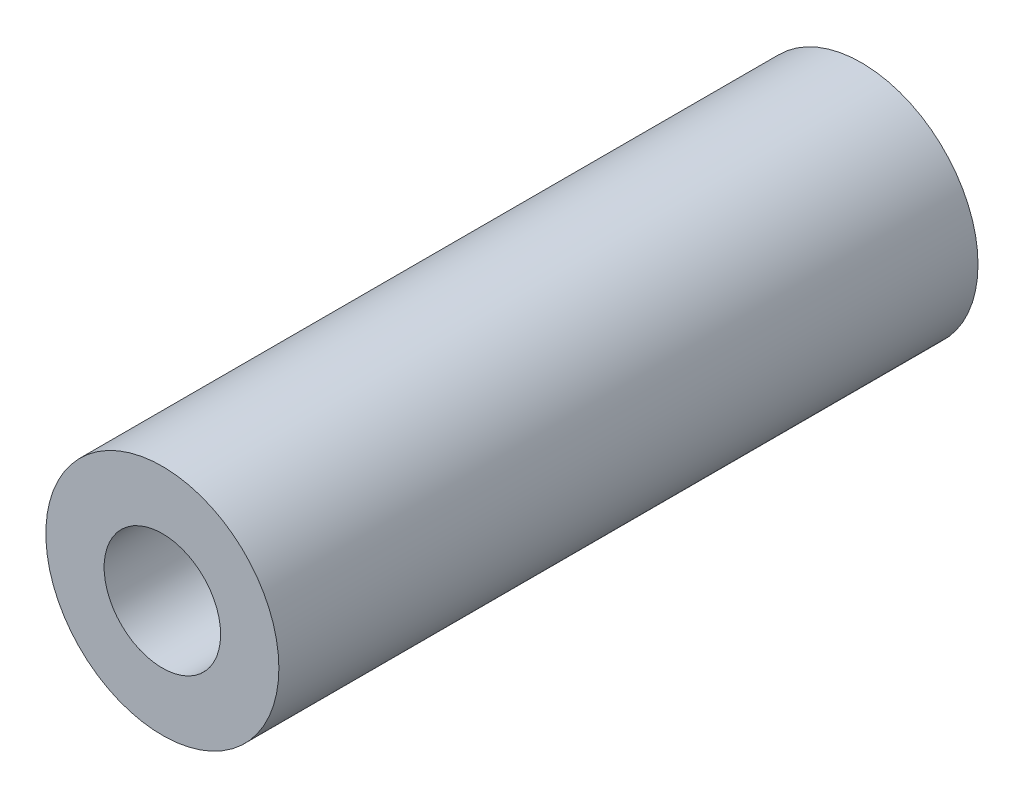
SolidWorks part; units mm, degrees
ref_plane "Front Plane" through (0, 0, 0) normal (0, 0, 1) x (1, 0, 0)
ref_plane "Top Plane" through (0, 0, 0) normal (0, 1, 0) x (1, 0, 0)
ref_plane "Right Plane" through (0, 0, 0) normal (1, 0, 0) x (0, 0, -1)
sketch "Sketch1" plane through (0, 0, 0) normal (0, 0, 1) x (1, 0, 0)
  circle A0 centre (0, 0) radius 25
  dimension "D1" = 50
  dimension "D2" = 0
extrude "Boss-Extrude1" add sketch "Sketch1" along normal blind 150
sketch "Sketch3" plane through (0, 0, 150) normal (0, 0, 1) x (1, 0, 0)
  circle A0 centre (0, 0) radius 12.5
  dimension "D1" = 25
extrude "Cut-Extrude2" cut sketch "Sketch3" against normal blind 100
